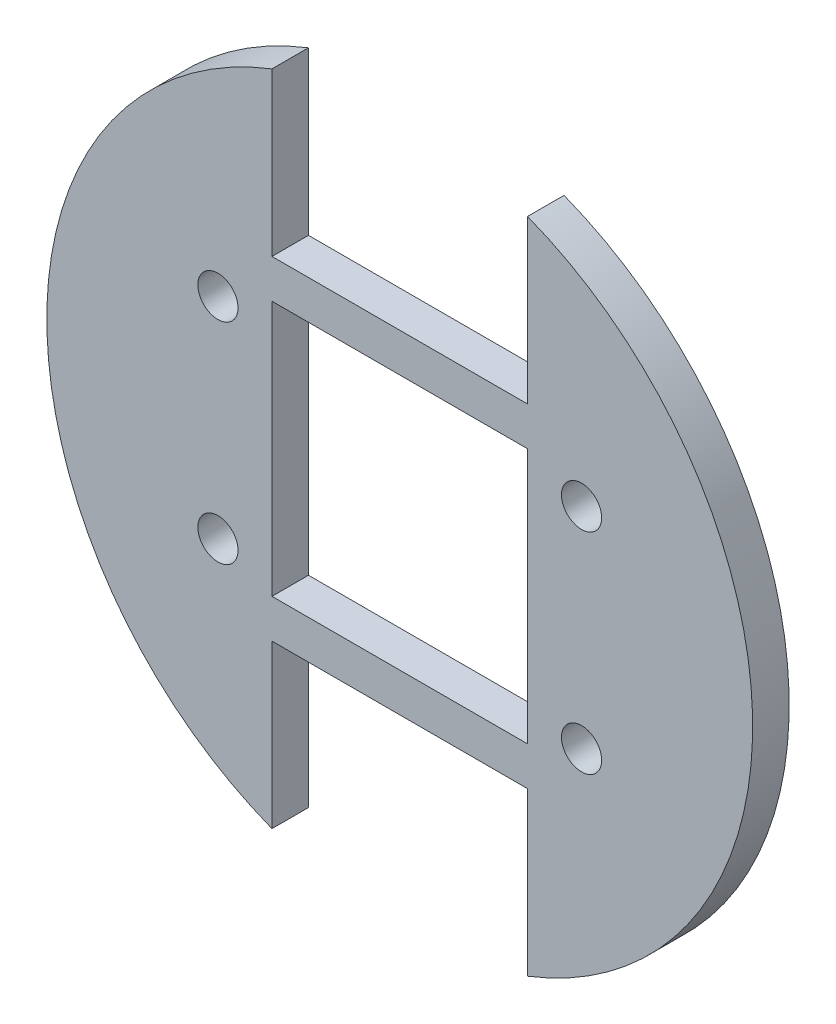
SolidWorks part; units mm, degrees
ref_plane "前视基准面" through (0, 0, 0) normal (0, 0, 1) x (1, 0, 0)
ref_plane "上视基准面" through (0, 0, 0) normal (0, 1, 0) x (1, 0, 0)
ref_plane "右视基准面" through (0, 0, 0) normal (1, 0, 0) x (0, 0, -1)
other "Configuration Table"
sketch "草图1" plane through (0, 0, 0) normal (0, 0, 1) x (1, 0, 0)
  line L0 (55, 0) -> (-55, 0) construction
  line L5 (-10.5, 10.5) -> (10.5, 10.5)
  line L6 (-10.5, 10.5) -> (-10.5, -10.5)
  line L9 (-10.5, -10.5) -> (10.5, -10.5)
  line L10 (10.5, 10.5) -> (10.5, -10.5)
  line L11 (-10.5, 10.5) -> (10.5, -10.5) construction
  line L12 (-10.5, -10.5) -> (10.5, 10.5) construction
  line L13 (10.5, -13.6862) -> (10.5, -27.0324)
  line L14 (-10.5, 27.0324) -> (-10.5, 13.6862)
  line L15 (-10.5, 13.6862) -> (10.5, 13.6862)
  line L16 (10.5, 13.6862) -> (10.5, 27.0324)
  line L17 (-10.5, -13.6862) -> (10.5, -13.6862)
  line L18 (-10.5, -27.0324) -> (-10.5, -13.6862)
  arc A10 (-10.5, 27.0324) -> (-10.5, -27.0324) centre (0, 0) ccw
  arc A11 (-10.5, 13.6862) -> (-10.5, -13.6862) centre (0, 0) ccw construction
  circle A18 centre (14.9389, 8.625) radius 1.65
  circle A19 centre (14.9389, -8.625) radius 1.65
  circle A21 centre (-14.9389, -8.625) radius 1.65
  circle A22 centre (-14.9389, 8.625) radius 1.65
  arc A24 (10.5, -27.0324) -> (10.5, 27.0324) centre (0, 0) ccw
  arc A25 (10.5, -13.6862) -> (10.5, 13.6862) centre (0, 0) ccw construction
  point P16 (0, 0)
  point P20 (0, 0)
  dimension "D1" = 58
  dimension "D2" = 34.5
  dimension "D5" = 21
  dimension "D6" = 21
extrude "凸台-拉伸1" add sketch "草图1" along normal blind 3
